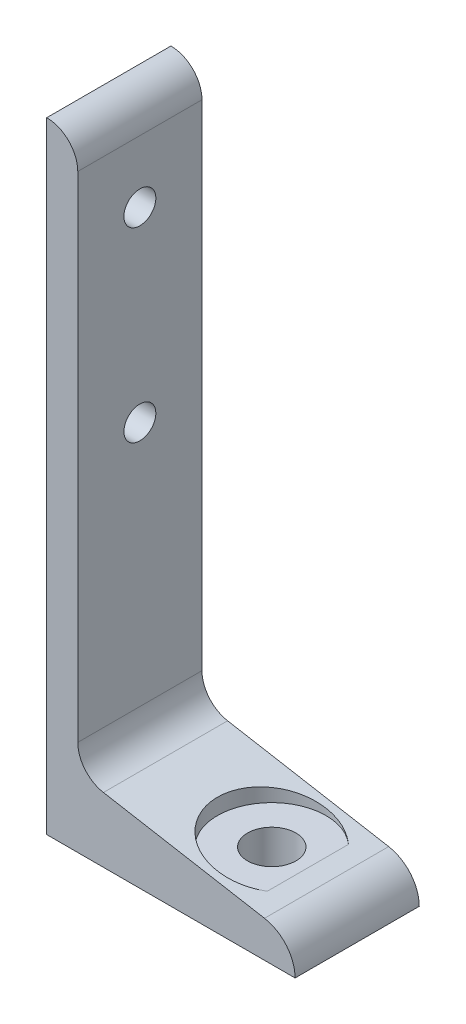
SolidWorks part; units mm, degrees
ref_plane "Front Plane" through (0, 0, 0) normal (0, 0, 1) x (1, 0, 0)
ref_plane "Top Plane" through (0, 0, 0) normal (0, 1, 0) x (1, 0, 0)
ref_plane "Right Plane" through (0, 0, 0) normal (1, 0, 0) x (0, 0, -1)
sketch "Sketch1" plane through (0, 0, 0) normal (0, 0, 1) x (1, 0, 0)
  line L0 (0, 0) -> (0, 127)
  line L1 (6.35, 127) -> (6.35, 120.65) construction
  line L2 (6.35, 120.65) -> (6.35, 19.516)
  line L3 (11.5973, 13.2625) -> (44.5465, 7.4527)
  line L4 (6.35, 127) -> (0, 127) construction
  line L5 (50.8, 0) -> (0, 0)
  line L6 (44.5465, 7.4527) -> (50.8, 6.35) construction
  line L7 (50.8, 6.35) -> (50.8, 0) construction
  arc A0 (6.35, 120.65) -> (0, 127) centre (0, 120.65) ccw
  arc A1 (50.8, 0) -> (44.5465, 7.4527) centre (43.2324, 0) ccw
  arc A2 (6.35, 19.516) -> (11.5973, 13.2625) centre (12.7, 19.516) ccw
  point P2 (6.35, 123.825)
  dimension "D1" = 10
  dimension "E" = 6.35
  dimension "Er" = 6.35
  dimension "Dr" = 6.35
  dimension "A" = 127
  dimension "F" = 50.8
extrude "Boss-Extrude1" add sketch "Sketch1" along normal mid plane 25.4
sketch "Sketch2" plane through (0, 0, 0) normal (0, 1, 0) x (1, 0, 0)
  line L0 (0, -12.7) -> (50.8, -12.7) construction
  line L2 (33.3248, 0) -> (0, 0) construction
  line L3 (0, -12.7) -> (0, 12.7) construction
  line L4 (33.3248, 0) -> (33.3248, 25.4) construction
  line L5 (50.8, -12.7) -> (50.8, 12.7) construction
  circle A0 centre (33.3248, 0) radius 4.953
  circle A1 centre (33.3248, 0) radius 11.1125 construction
  dimension "L" = 9.906
  dimension "M" = 22.225
  dimension "N" = 12.7
  dimension "G" = 17.4752
  dimension "H" = 25.4
extrude "Cut-Extrude1" cut sketch "Sketch2" along normal through all
sketch "Sketch3" plane through (0, 0, 0) normal (0, 1, 0) x (1, 0, 0)
  circle A1 centre (33.3248, 0) radius 11.1125 construction
  circle A2 centre (33.3248, 0) radius 11.1125
extrude "Cut-Extrude2" cut sketch "Sketch3" along normal through all from offset 8.128
sketch "Sketch4" plane through (0, 0, 0) normal (1, 0, 0) x (0, 0, -1)
  line L0 (0, 0) -> (0, 69.85) construction
  line L1 (0, 69.85) -> (0, 107.95) construction
  line L2 (0, 107.95) -> (25.4, 107.95) construction
  circle A0 centre (0, 69.85) radius 3.2639
  circle A1 centre (0, 107.95) radius 3.2639
  dimension "K" = 6.5278
  dimension "B" = 69.85
  dimension "C" = 38.1
  dimension "D" = 25.4
extrude "Cut-Extrude3" cut sketch "Sketch4" along normal through all
pattern_linear "LPattern1" [suppressed] count 2 spacing 25.4 along (0, 0, -1)
pattern_linear "LPattern2" [suppressed] count 2 spacing 25.4 along (0, 0, -1)
equation "\"D3@LPattern1\" = \"H@Sketch2\""
equation "\"D3@LPattern2\" = \"D@Sketch4\""
